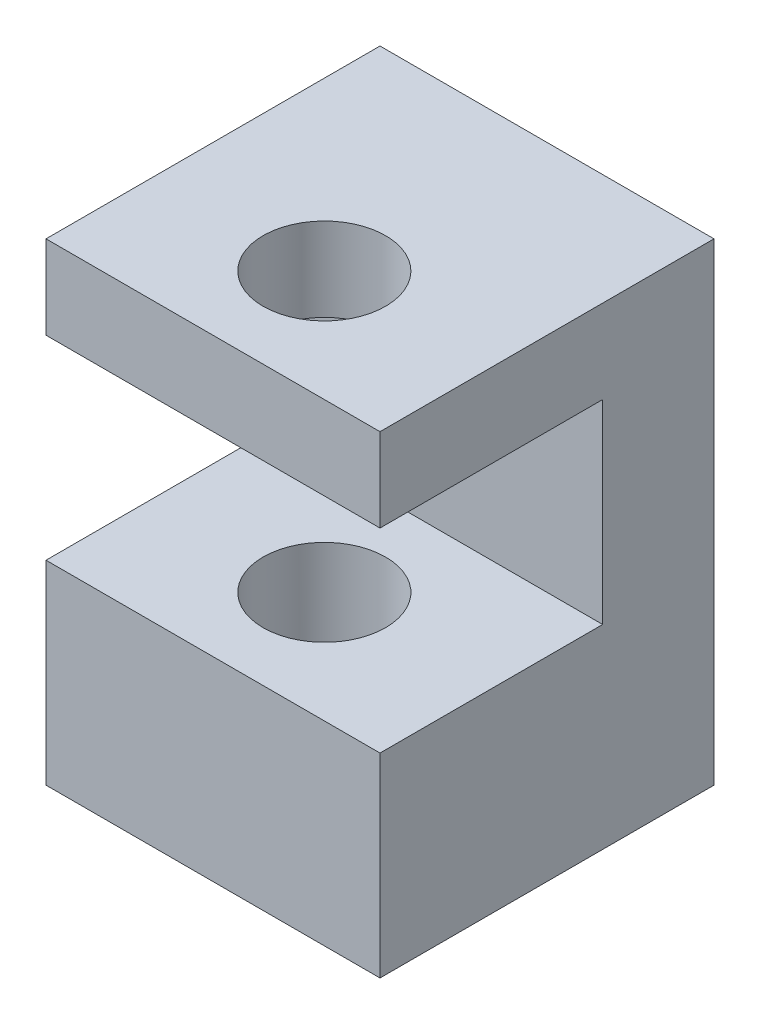
SolidWorks part; units mm, degrees
ref_plane "Front" through (0, 0, 0) normal (0, 0, 1) x (1, 0, 0)
ref_plane "Top" through (0, 0, 0) normal (0, 1, 0) x (1, 0, 0)
ref_plane "Right" through (0, 0, 0) normal (1, 0, 0) x (0, 0, -1)
sketch "Sketch1" plane through (0, 0, 0) normal (0, 1, 0) x (1, 0, 0)
  line L1 (0, 0) -> (60, 0)
  line L2 (0, 0) -> (0, 60)
  line L3 (0, 60) -> (60, 60)
  line L4 (60, 0) -> (60, 60)
  dimension "D1" = 60
  dimension "D2" = 60
extrude "Boss-Extrude1" add sketch "Sketch1" along normal blind 85
sketch "Sketch2" plane through (60, 0, 0) normal (1, 0, 0) x (0, 0, -1)
  line L0 (0, 85) -> (0, 0) construction
  line L1 (0, 70) -> (40, 70)
  line L2 (0, 70) -> (0, 35)
  line L3 (0, 35) -> (40, 35)
  line L4 (40, 70) -> (40, 35)
  line L5 (0, 42.5) -> (60, 42.5) construction
  line L6 (60, 85) -> (60, 0) construction
  line L8 (0, 85) -> (60, 85) construction
  dimension "D1" = 15
  dimension "D2" = 40
  dimension "D3" = 35
extrude "Cut-Extrude1" cut sketch "Sketch2" against normal through all
sketch "Sketch3" plane through (0, 35, 0) normal (0, 1, 0) x (1, 0, 0)
  line L0 (0, 20) -> (60, 20) construction
  line L1 (0, 0) -> (0, 40) construction
  line L2 (60, 0) -> (60, 40) construction
  circle A0 centre (30, 20) radius 11
  dimension "D1" = 22
extrude "Cut-Extrude2" cut sketch "Sketch3" against normal through all both and the other way through all
